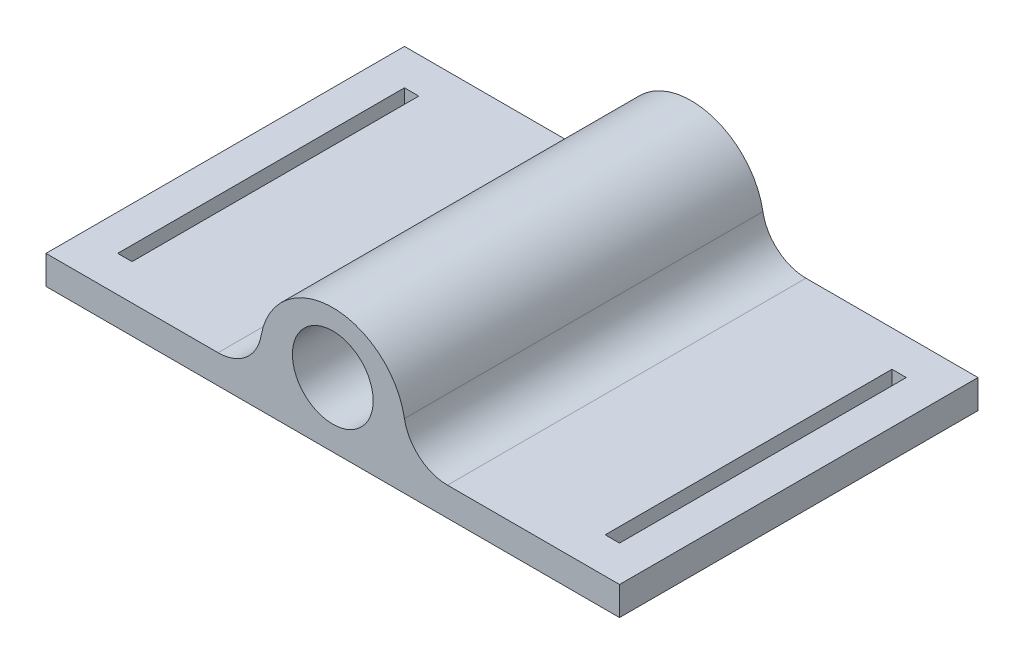
SolidWorks part; units mm, degrees
ref_plane "Front Plane" through (0, 0, 0) normal (0, 0, 1) x (1, 0, 0)
ref_plane "Top Plane" through (0, 0, 0) normal (0, 1, 0) x (1, 0, 0)
ref_plane "Right Plane" through (0, 0, 0) normal (1, 0, 0) x (0, 0, -1)
sketch "Sketch1" plane through (0, 0, 0) normal (0, 0, 1) x (1, 0, 0)
  line L0 (-4.1227, 0) -> (-4.1227, 2)
  line L1 (-4.1227, 0) -> (35.8773, 0)
  line L2 (35.8773, 0) -> (35.8773, 2)
  line L3 (35.8773, 2) -> (23.8773, 2)
  line L4 (-4.1227, 2) -> (7.8773, 2)
  arc A0 (7.8773, 2) -> (10.8773, 4.5218) centre (7.8773, 5.0453) ccw
  arc A1 (23.8773, 2) -> (20.8773, 4.5218) centre (23.8773, 5.0453) cw
  arc A2 (10.8773, 4.5218) -> (20.8773, 4.5218) centre (15.8773, 3.6491) cw
  point P12 (0, 0)
  point P13 (0, 0)
  point P14 (0, 0)
  dimension "D1" = 2
  dimension "D2" = 40
  dimension "D3" = 12
  dimension "D4" = 12
  dimension "D5" = 3
  dimension "D6" = 3
extrude "Boss-Extrude2" add sketch "Sketch1" along normal blind 25
sketch "Sketch3" plane through (0, 0, 0) normal (0, 1, 0) x (1, 0, 0)
  line L1 (-1.6227, -2.5) -> (-0.6227, -2.5)
  line L2 (-1.6227, -2.5) -> (-1.6227, -22.5)
  line L3 (-1.6227, -22.5) -> (-0.6227, -22.5)
  line L4 (-0.6227, -2.5) -> (-0.6227, -22.5)
  line L5 (7.8773, 0) -> (-4.1227, 0) construction
  line L7 (-4.1227, -25) -> (-4.1227, 0) construction
  line L8 (35.8773, 0) -> (23.8773, 0) construction
  line L9 (32.3773, -2.5) -> (33.3773, -2.5)
  line L10 (32.3773, -2.5) -> (32.3773, -22.5)
  line L11 (32.3773, -22.5) -> (33.3773, -22.5)
  line L12 (33.3773, -2.5) -> (33.3773, -22.5)
  line L13 (35.8773, -25) -> (35.8773, 0) construction
  dimension "D1" = 20
  dimension "D2" = 2.5
  dimension "D3" = 1
  dimension "D4" = 2.5
  dimension "D5" = 20
  dimension "D6" = 1
  dimension "D7" = 2.5
  dimension "D8" = 2.5
extrude "Cut-Extrude2" cut sketch "Sketch3" along normal blind 5
sketch "Sketch4" plane through (0, 0, 25) normal (0, 0, 1) x (1, 0, 0)
  line L0 (-4.1227, 0) -> (35.8773, 0) construction
  circle A0 centre (15.8773, 4.5) radius 2.8172
  dimension "D1" = 4.5
extrude "Cut-Extrude3" cut sketch "Sketch4" against normal blind 36
